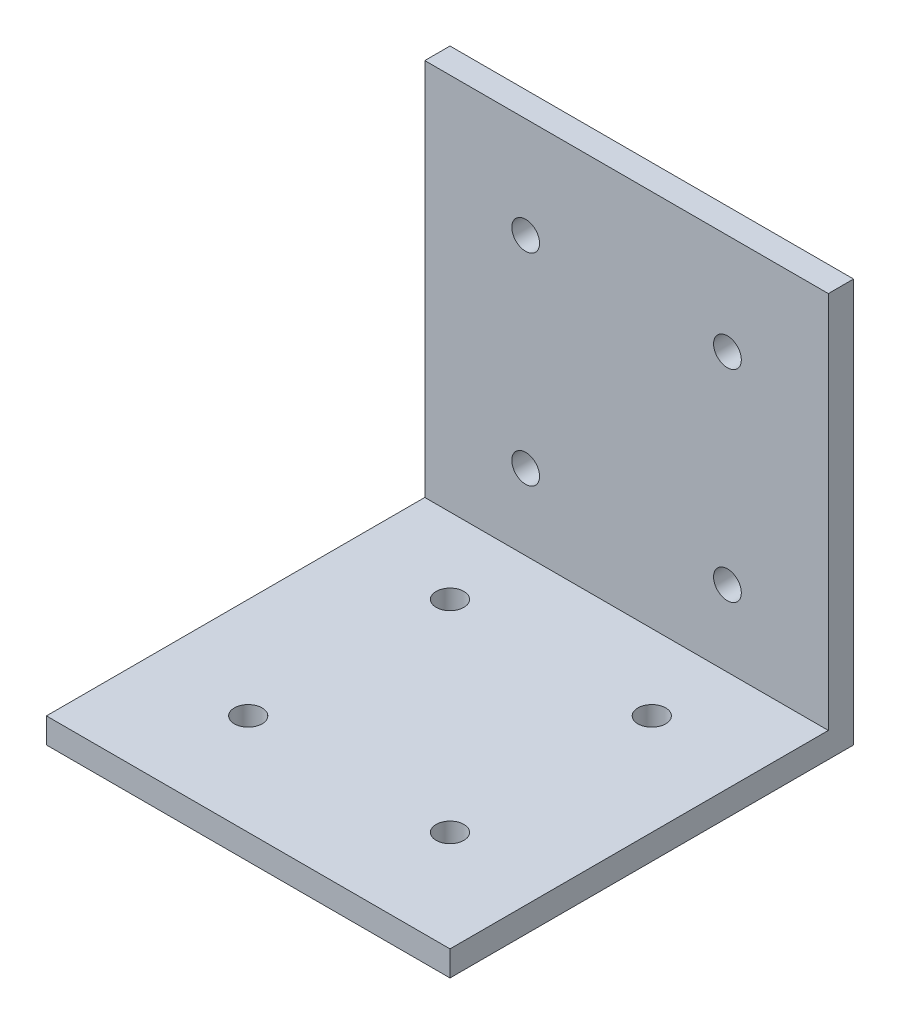
SolidWorks part; units mm, degrees
ref_plane "Front Plane" through (0, 0, 0) normal (0, 0, 1) x (1, 0, 0)
ref_plane "Top Plane" through (0, 0, 0) normal (0, 1, 0) x (1, 0, 0)
ref_plane "Right Plane" through (0, 0, 0) normal (1, 0, 0) x (0, 0, -1)
sketch "Sketch1" plane through (0, 0, 0) normal (0, 1, 0) x (1, 0, 0)
  line L1 (-50.8, 50.8) -> (50.8, 50.8)
  line L2 (-50.8, 50.8) -> (-50.8, -50.8)
  line L3 (-50.8, -50.8) -> (50.8, -50.8)
  line L4 (50.8, 50.8) -> (50.8, -50.8)
  line L5 (-50.8, 50.8) -> (50.8, -50.8) construction
  line L6 (-50.8, -50.8) -> (50.8, 50.8) construction
  line L11 (-30.4379, 30.4379) -> (30.4379, -30.4379) construction
  line L12 (-30.4379, -30.4379) -> (30.4379, 30.4379) construction
  line L13 (-25.4, 25.4) -> (25.4, 25.4) construction
  line L14 (-25.4, 25.4) -> (-25.4, -25.4) construction
  line L15 (-25.4, -25.4) -> (25.4, -25.4) construction
  line L16 (25.4, 25.4) -> (25.4, -25.4) construction
  line L17 (-25.4, 25.4) -> (25.4, -25.4) construction
  line L18 (-25.4, -25.4) -> (25.4, 25.4) construction
  circle A0 centre (-25.4, 25.4) radius 3.4925
  circle A1 centre (25.4, 25.4) radius 3.4925
  circle A2 centre (25.4, -25.4) radius 3.4925
  circle A3 centre (-25.4, -25.4) radius 3.4925
  point P0 (0, 0)
  point P6 (0, 0)
  point P12 (0, 0)
  point P20 (0, 0)
  dimension "D5" = 6.985
  dimension "D1" = 101.6
  dimension "D2" = 101.6
  dimension "D3" = 50.8
  dimension "D4" = 50.8
extrude "Boss-Extrude1" add sketch "Sketch1" along normal blind 6.35
sketch "Sketch2" plane through (0, 6.35, 0) normal (0, 1, 0) x (1, 0, 0)
  line L0 (50.8, -50.8) -> (50.8, 50.8) construction
  line L1 (-50.8, 50.8) -> (50.8, 50.8)
  line L2 (-50.8, 50.8) -> (-50.8, 44.45)
  line L3 (-50.8, 44.45) -> (50.8, 44.45)
  line L4 (50.8, 50.8) -> (50.8, 44.45)
  dimension "D1" = 6.35
extrude "Boss-Extrude2" add sketch "Sketch2" along normal blind 95.25
sketch "Sketch3" plane through (0, 0, -50.8) normal (0, 0, -1) x (-1, 0, 0)
  line L0 (-50.8, 0) -> (50.8, 0) construction
  line L1 (-25.4, 76.2) -> (25.4, 76.2) construction
  line L2 (-25.4, 76.2) -> (-25.4, 25.4) construction
  line L3 (-25.4, 25.4) -> (25.4, 25.4) construction
  line L4 (25.4, 76.2) -> (25.4, 25.4) construction
  line L5 (-25.4, 76.2) -> (25.4, 25.4) construction
  line L6 (-25.4, 25.4) -> (25.4, 76.2) construction
  circle A0 centre (-25.4, 76.2) radius 3.4925
  circle A1 centre (25.4, 76.2) radius 3.4925
  circle A2 centre (25.4, 25.4) radius 3.4925
  circle A3 centre (-25.4, 25.4) radius 3.4925
  point P0 (0, 50.8)
  dimension "D4" = 6.985
  dimension "D1" = 25.4
  dimension "D2" = 50.8
  dimension "D3" = 50.8
extrude "Cut-Extrude1" cut sketch "Sketch3" against normal up to surface (6.35 mm away) up to face at (0, 53.975, -44.45)
